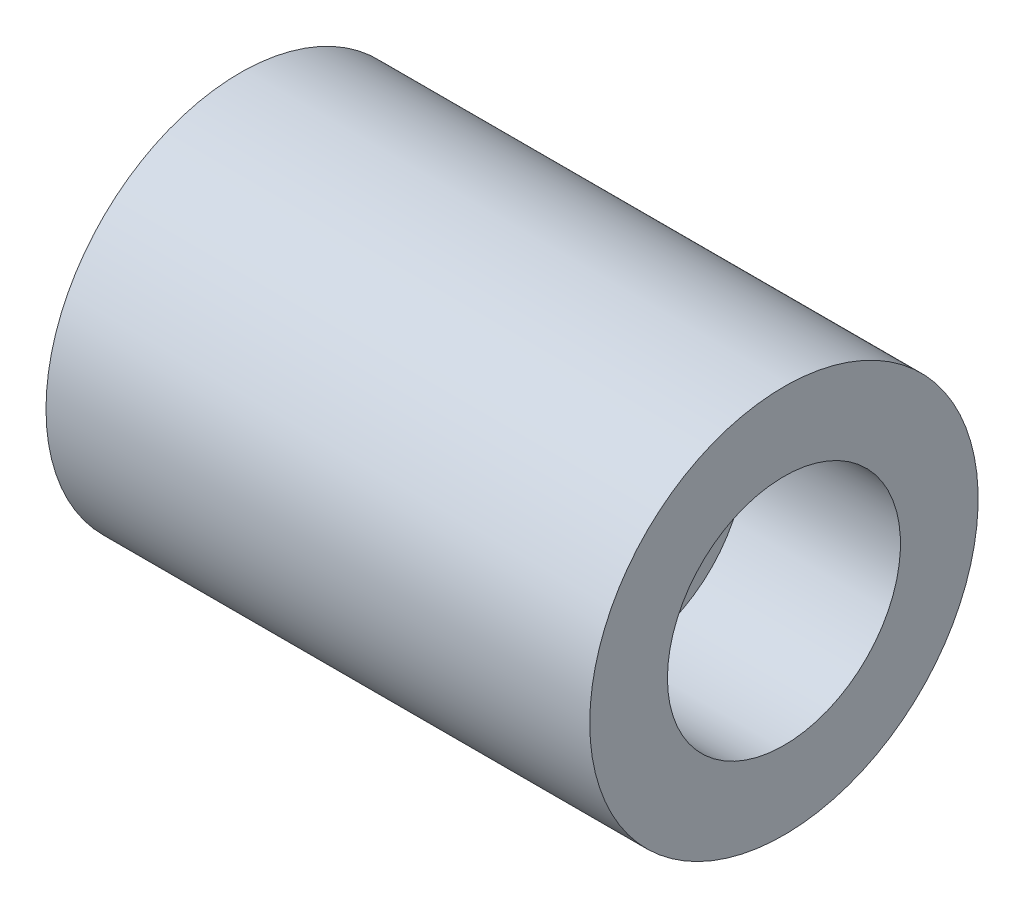
SolidWorks part; units mm, degrees
ref_plane "Front Plane" through (0, 0, 0) normal (0, 0, 1) x (1, 0, 0)
ref_plane "Top Plane" through (0, 0, 0) normal (0, 1, 0) x (1, 0, 0)
ref_plane "Right Plane" through (0, 0, 0) normal (1, 0, 0) x (0, 0, -1)
sketch "Sketch1" plane through (0, 0, 0) normal (0, 0, 1) x (1, 0, 0)
  line L0 (0, 50) -> (0, 30)
  line L1 (0, 50) -> (-140, 50)
  line L2 (-140, 50) -> (-140, 0)
  line L3 (-140, 0) -> (-120, 0)
  line L4 (-120, 0) -> (-120, 10)
  line L5 (-120, 10) -> (-40, 10)
  line L6 (-40, 10) -> (-40, 30)
  line L7 (-40, 30) -> (0, 30)
  line L8 (-205.2771, 0) -> (53.9563, 0) construction
  dimension "D1" = 40
  dimension "D2" = 80
  dimension "D3" = 20
  dimension "D4" = 50
  dimension "D5" = 10
  dimension "D6" = 20
sketch "Sketch2" plane through (0, 0, 0) normal (0, 0, 1) x (1, 0, 0)
revolve "Revolve1" add sketch "Sketch1" angle 360 about L8
